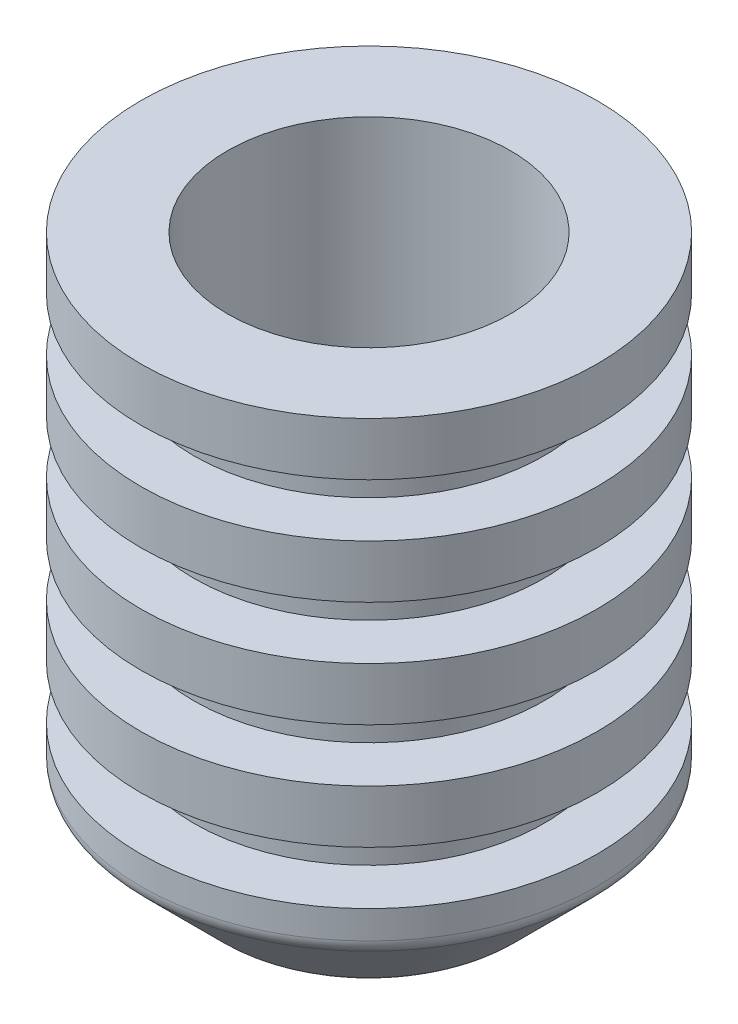
SolidWorks part; units mm, degrees
material "硅橡胶"
ref_plane "前视基准面" through (0, 0, 0) normal (0, 0, 1) x (1, 0, 0)
ref_plane "上视基准面" through (0, 0, 0) normal (0, 1, 0) x (1, 0, 0)
ref_plane "右视基准面" through (0, 0, 0) normal (1, 0, 0) x (0, 0, -1)
sketch "草图1" plane through (0, 0, 0) normal (0, 1, 0) x (1, 0, 0)
  circle A0 centre (0, 0) radius 12.9
  dimension "D1" = 25.8
extrude "凸台-拉伸1" add sketch "草图1" along normal blind 31 contours A0
sketch "草图2" plane through (0, 31, 0) normal (0, 1, 0) x (1, 0, 0)
  circle A0 centre (0, 0) radius 8
  dimension "D1" = 16
extrude "切除-拉伸1" cut sketch "草图2" against normal blind 25
chamfer "倒角1" distance 5 angle 45 1 edges at (0, 0, 12.9)
fillet "圆角1" radius 1 2 edges at (0, 5, 12.9) (0, 0, 7.9)
sketch "草图3" plane through (0, 0, 0) normal (0, 0, 1) x (1, 0, 0)
  line L0 (0, 0) -> (0, 31) construction
  line L1 (12.9, 31) -> (-12.9, 31) construction
  line L2 (12.9, 5.4142) -> (12.9, 31) construction
  line L3 (12.9, 28) -> (9.9, 28)
  line L4 (12.9, 28) -> (12.9, 25)
  line L5 (12.9, 25) -> (9.9, 25)
  line L6 (9.9, 28) -> (9.9, 25)
  line L7 (12.9, 28) -> (9.9, 25) construction
  line L8 (12.9, 25) -> (9.9, 28) construction
  line L9 (12.9, 22) -> (12.9, 19)
  line L10 (12.9, 22) -> (9.9, 22)
  line L11 (9.9, 22) -> (9.9, 19)
  line L12 (12.9, 19) -> (9.9, 19)
  line L13 (12.9, 16) -> (12.9, 13)
  line L14 (12.9, 16) -> (9.9, 16)
  line L15 (9.9, 16) -> (9.9, 13)
  line L16 (12.9, 13) -> (9.9, 13)
  line L17 (12.9, 10) -> (12.9, 7)
  line L18 (12.9, 10) -> (9.9, 10)
  line L19 (9.9, 10) -> (9.9, 7)
  line L20 (12.9, 7) -> (9.9, 7)
  point P5 (11.4, 26.5)
  dimension "D1" = 3
  dimension "D2" = 3
  dimension "D3" = 3
  dimension "D5" = 3
  dimension "D4" = 4
revolve "切除-旋转1" cut sketch "草图3" angle 360 about L0
